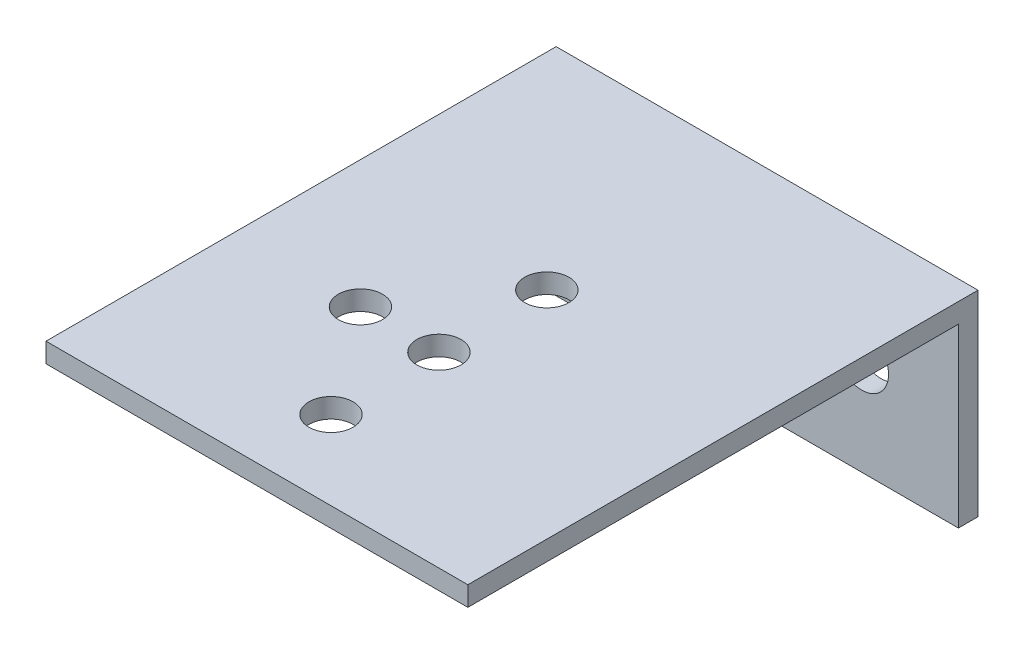
SolidWorks part; units mm, degrees
ref_plane "Plan de face" through (0, 0, 0) normal (0, 0, 1) x (1, 0, 0)
ref_plane "Plan de dessus" through (0, 0, 0) normal (0, 1, 0) x (1, 0, 0)
ref_plane "Plan de droite" through (0, 0, 0) normal (1, 0, 0) x (0, 0, -1)
sketch "Esquisse1" plane through (0, 0, 0) normal (0, 0, 1) x (1, 0, 0)
  line L1 (-21.5, -10) -> (21.5, -10)
  line L2 (-21.5, -10) -> (-21.5, 10)
  line L3 (-21.5, 10) -> (21.5, 10)
  line L4 (21.5, -10) -> (21.5, 10)
  line L5 (-21.5, -10) -> (21.5, 10) construction
  line L6 (-21.5, 10) -> (21.5, -10) construction
  point P0 (0, 0)
  dimension "D1" = 20
  dimension "D2" = 43
extrude "Boss.-Extru.1" add sketch "Esquisse1" along normal blind 52
sketch "Esquisse2" plane through (0, 0, 52) normal (0, 0, 1) x (1, 0, 0)
  line L12 (19.5, -8) -> (19.5, 8)
  line L13 (19.5, 8) -> (-19.5, 8)
  line L14 (-19.5, 8) -> (-19.5, -8)
  line L15 (-19.5, -8) -> (19.5, -8)
  line L16 (30.2089, -13.9443) -> (30.2089, 8)
  line L17 (30.2089, 8) -> (-27.0688, 8)
  line L18 (-27.0688, 8) -> (-27.0688, -13.9443)
  line L19 (-27.0688, -13.9443) -> (30.2089, -13.9443)
  dimension "D1" = 2
extrude "Enlèv. mat.-Extru.1" cut sketch "Esquisse2" against normal blind 50
hole_wizard "Dégagement M41" positions "Esquisse4" profile "Esquisse3" hole size "M4" standard "JIS" end condition through all
sketch "Esquisse4" plane through (0, 10, 0) normal (0, 1, 0) x (1, 0, 0)
  point P0 (-0.5, -21.95)
  point P2 (-0.5, -32.95)
  point P3 (-0.5, -43.95)
  point P5 (-8.5, -32.95)
sketch "Esquisse3" plane through (-0.5, 10, 21.95) normal (1, 0, 0) x (0, 0, 1)
  line L0 (0, 0) -> (0, 20)
  line L1 (0, 20) -> (2.25, 20)
  line L2 (2.25, 20) -> (2.25, 0)
  line L5 (2.25, 0) -> (0, 0)
  line L11 (0, -6.35) -> (0, 107.95) construction
  dimension "Diamètre du perçage jusqu'au prochain" = 4.5
  dimension "Profondeur du perçage jusqu'au prochain" = 20
hole_wizard "Dégagement M51" positions "Esquisse7" profile "Esquisse5" hole size "M5" standard "JIS" end condition through all
sketch "Esquisse7" plane through (0, 0, 0) normal (0, 0, -1) x (-1, 0, 0)
  point P0 (-11.6327, 0)
  point P3 (8.6866, 0)
sketch "Esquisse5" plane through (11.6327, 0, 0) normal (1, 0, 0) x (0, 1, 0)
  line L0 (0, 0) -> (0, 52)
  line L1 (0, 52) -> (2.75, 52)
  line L2 (2.75, 52) -> (2.75, 0)
  line L5 (2.75, 0) -> (0, 0)
  line L11 (0, -6.35) -> (0, 107.95) construction
  dimension "Diamètre du perçage jusqu'au prochain" = 5.5
  dimension "Profondeur du perçage jusqu'au prochain" = 52
